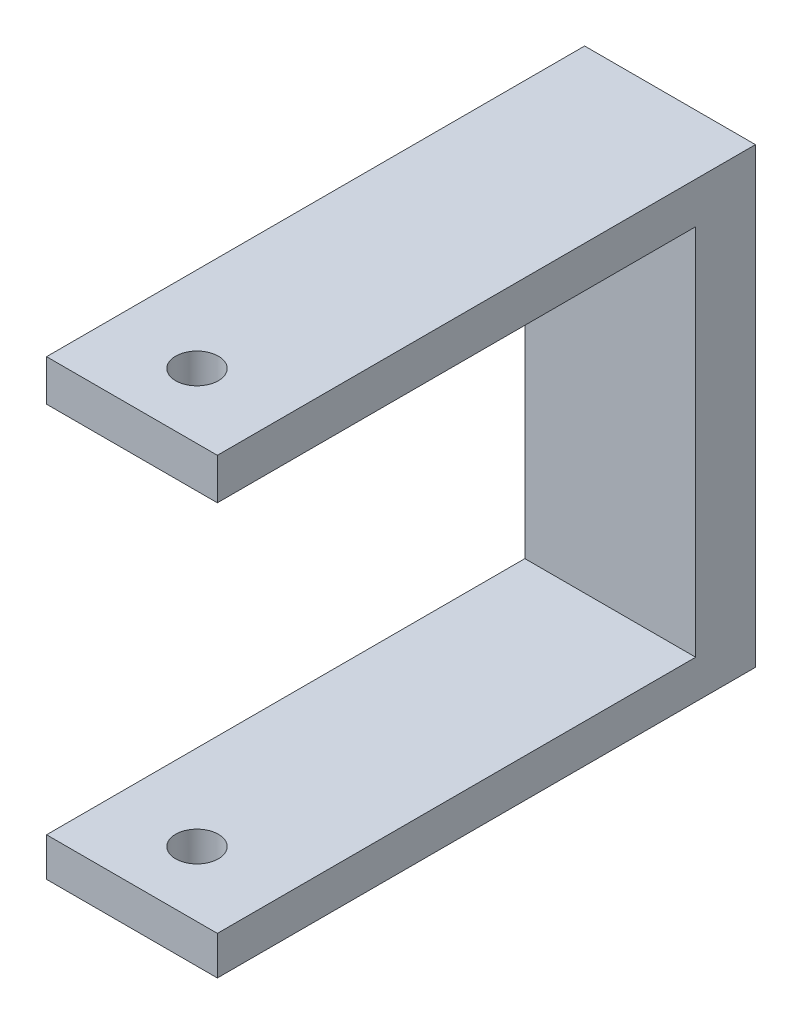
SolidWorks part; units mm, degrees
ref_plane "Front Plane" through (0, 0, 0) normal (0, 0, 1) x (1, 0, 0)
ref_plane "Top Plane" through (0, 0, 0) normal (0, 1, 0) x (1, 0, 0)
ref_plane "Right Plane" through (0, 0, 0) normal (1, 0, 0) x (0, 0, -1)
sketch "Sketch1" plane through (0, 0, 0) normal (0, 1, 0) x (1, 0, 0)
  line L1 (-10, 50) -> (10, 50)
  line L2 (-10, 50) -> (-10, -50)
  line L3 (-10, -50) -> (10, -50)
  line L4 (10, 50) -> (10, -50)
  line L5 (-10, 50) -> (10, -50) construction
  line L6 (-10, -50) -> (10, 50) construction
  point P0 (0, 0)
extrude "Boss-Extrude1" add sketch "Sketch1" along normal blind 53
sketch "Sketch2" plane through (0, 0, 50) normal (0, 0, 1) x (1, 0, 0)
  line L0 (10, 53) -> (10, 0) construction
  line L1 (10, 4.5241) -> (-10, 4.5241)
  line L2 (10, 4.5241) -> (10, 26.6393)
  line L3 (10, 26.6393) -> (-10, 26.6393)
  line L4 (-10, 4.5241) -> (-10, 26.6393)
  line L5 (-10, 53) -> (-10, 0) construction
extrude "Cut-Extrude1" cut sketch "Sketch2" against normal blind 93
sketch "Sketch3" plane through (0, 53, 0) normal (0, 1, 0) x (1, 0, 0)
  circle A0 centre (0, -43.3397) radius 2.5
extrude "Cut-Extrude2" cut sketch "Sketch3" against normal blind 93
sketch "Sketch4" plane through (0, 0, 50) normal (0, 0, 1) x (1, 0, 0)
  line L0 (-10, 53) -> (-10, 26.6393) construction
  line L1 (10, 26.6393) -> (-10, 26.6393)
  line L2 (10, 26.6393) -> (10, 34.0679)
  line L3 (10, 34.0679) -> (-10, 34.0679)
  line L4 (-10, 26.6393) -> (-10, 34.0679)
extrude "Cut-Extrude3" cut sketch "Sketch4" against normal blind 93
sketch "Sketch5" plane through (0, 0, 50) normal (0, 0, 1) x (1, 0, 0)
  line L0 (-10, 53) -> (-10, 34.0679) construction
  line L1 (10, 34.0679) -> (-10, 34.0679)
  line L2 (10, 34.0679) -> (10, 48.1796)
  line L3 (10, 48.1796) -> (-10, 48.1796)
  line L4 (-10, 34.0679) -> (-10, 48.1796)
extrude "Cut-Extrude4" cut sketch "Sketch5" against normal blind 93
sketch "Sketch6" plane through (0, 53, 0) normal (0, 1, 0) x (1, 0, 0)
  circle A0 centre (0, -5.3856) radius 2.5
extrude "Cut-Extrude5" cut sketch "Sketch6" against normal blind 70
sketch "Sketch7" plane through (0, 0, 50) normal (0, 0, 1) x (1, 0, 0)
  line L1 (-10, 53) -> (10, 53)
  line L2 (-10, 53) -> (-10, 0)
  line L3 (-10, 0) -> (10, 0)
  line L4 (10, 53) -> (10, 0)
extrude "Cut-Extrude6" cut sketch "Sketch7" against normal blind 37
